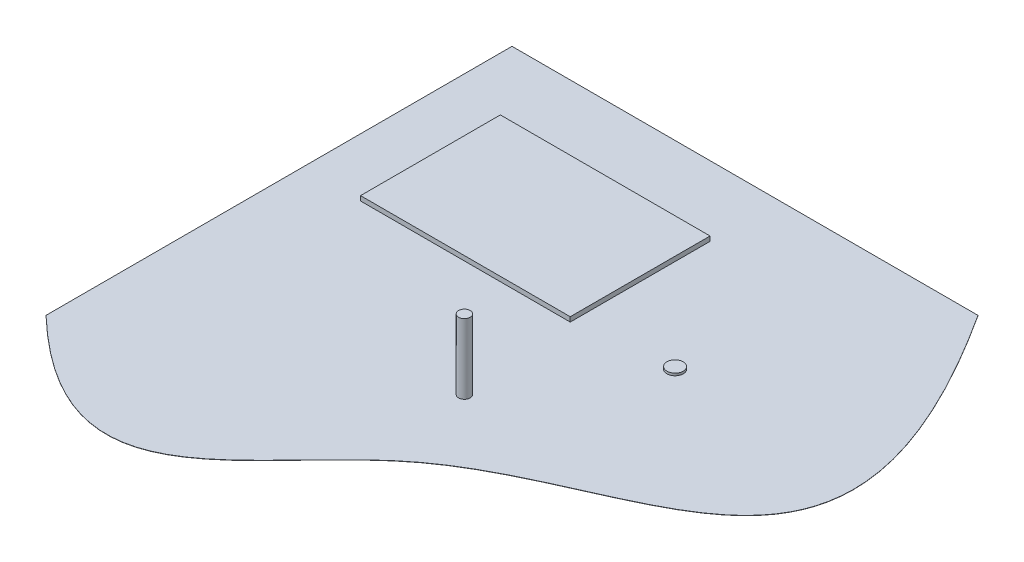
SolidWorks part; units mm, degrees
ref_plane "Спереди" through (0, 0, 0) normal (0, 0, 1) x (1, 0, 0)
ref_plane "Сверху" through (0, 0, 0) normal (0, 1, 0) x (1, 0, 0)
ref_plane "Справа" through (0, 0, 0) normal (1, 0, 0) x (0, 0, -1)
sketch "Эскиз1" plane through (0, 0, 0) normal (0, 1, 0) x (1, 0, 0)
  line L0 (0, 0) -> (20000, 0)
  line L1 (0, 0) -> (0, -20000)
  spline S0 degree 3 poles (0, -20000) (7198.3528, -26864.5196) (12070.5058, -12028.819) (29348.4021, -14440.6963) (20000, 0) knots 0 0 0 0 0.41356 1 1 1 1
  dimension "D1" = 20000
  dimension "D2" = 20000
extrude "Бобышка-Вытянуть1" add sketch "Эскиз1" along normal blind 10
sketch "Эскиз2" plane through (0, 10, 0) normal (0, 1, 0) x (1, 0, 0)
  line L0 (20000, 0) -> (0, 0) construction
  line L1 (2500, -3000) -> (11500, -3000)
  line L2 (2500, -3000) -> (2500, -9000)
  line L3 (2500, -9000) -> (11500, -9000)
  line L4 (11500, -3000) -> (11500, -9000)
  line L5 (0, 0) -> (0, -20000) construction
  dimension "D1" = 3000
  dimension "D2" = 2500
  dimension "D3" = 9000
  dimension "D4" = 6000
extrude "Бобышка-Вытянуть2" add sketch "Эскиз2" along normal blind 200
sketch "Эскиз3" plane through (0, 10, 0) normal (0, 1, 0) x (1, 0, 0)
  line L0 (11500, -9000) -> (11500, -3000) construction
  line L1 (2500, -9000) -> (11500, -9000) construction
  circle A0 centre (15500, -8500) radius 350
  dimension "D1" = 700
  dimension "D2" = 4000
  dimension "D3" = 500
extrude "Бобышка-Вытянуть3" add sketch "Эскиз3" along normal blind 100 separate body
sketch "Эскиз4" plane through (0, 10, 0) normal (0, 1, 0) x (1, 0, 0)
  circle A0 centre (11923.7679, -13966.1785) radius 250
  point P2 (11923.7679, -13966.1785)
  dimension "D1" = 500
extrude "Бобышка-Вытянуть4" add sketch "Эскиз4" along normal blind 3000 separate body
